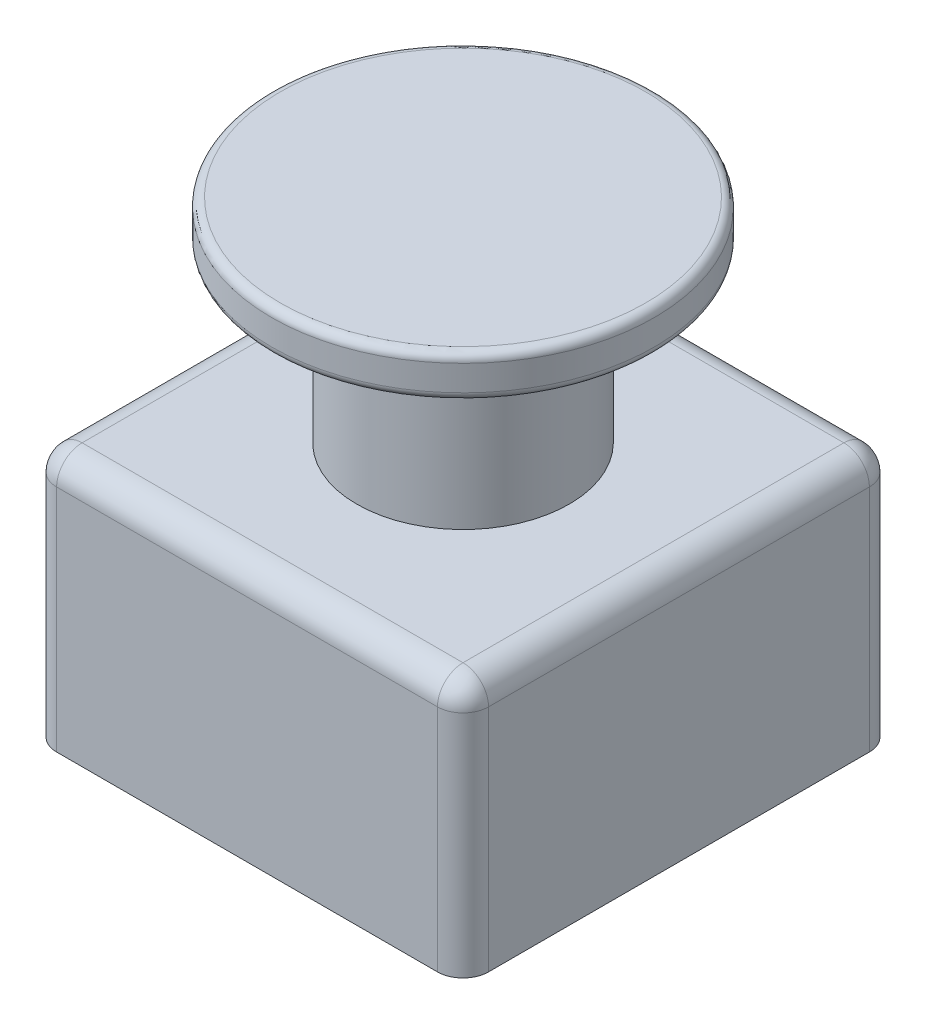
SolidWorks part; units mm, degrees
ref_plane "Front Plane" through (0, 0, 0) normal (0, 0, 1) x (1, 0, 0)
ref_plane "Top Plane" through (0, 0, 0) normal (0, 1, 0) x (1, 0, 0)
ref_plane "Right Plane" through (0, 0, 0) normal (1, 0, 0) x (0, 0, -1)
sketch "Sketch1" plane through (0, 0, 0) normal (0, 1, 0) x (1, 0, 0)
  line L1 (-25.4, 25.4) -> (25.4, 25.4)
  line L2 (-25.4, 25.4) -> (-25.4, -25.4)
  line L3 (-25.4, -25.4) -> (25.4, -25.4)
  line L4 (25.4, 25.4) -> (25.4, -25.4)
  line L5 (-25.4, 25.4) -> (25.4, -25.4) construction
  line L6 (-25.4, -25.4) -> (25.4, 25.4) construction
  point P0 (0, 0)
  dimension "D1" = 50.8
extrude "Boss-Extrude1" add sketch "Sketch1" against normal blind 30
sketch "Sketch2" plane through (0, 0, 0) normal (0, 1, 0) x (1, 0, 0)
  circle A0 centre (0, 0) radius 12.5
  dimension "D1" = 25
extrude "Boss-Extrude2" add sketch "Sketch2" along normal blind 20
sketch "Sketch3" plane through (0, 0, 0) normal (0, 1, 0) x (1, 0, 0)
  circle A0 centre (0, 0) radius 22.5
  dimension "D1" = 45
extrude "Boss-Extrude3" add sketch "Sketch3" along normal blind 5 from offset 20
fillet "Fillet1" radius 3 8 edges at (25.4, 0, 0) (0, 0, 25.4) (-25.4, 0, 0) (0, 0, -25.4) (25.4, -15, -25.4) (-25.4, -15, -25.4) (-25.4, -15, 25.4) (25.4, -15, 25.4)
fillet "Fillet2" radius 1 2 edges at (0, 20, 22.5) (0, 25, 22.5)
